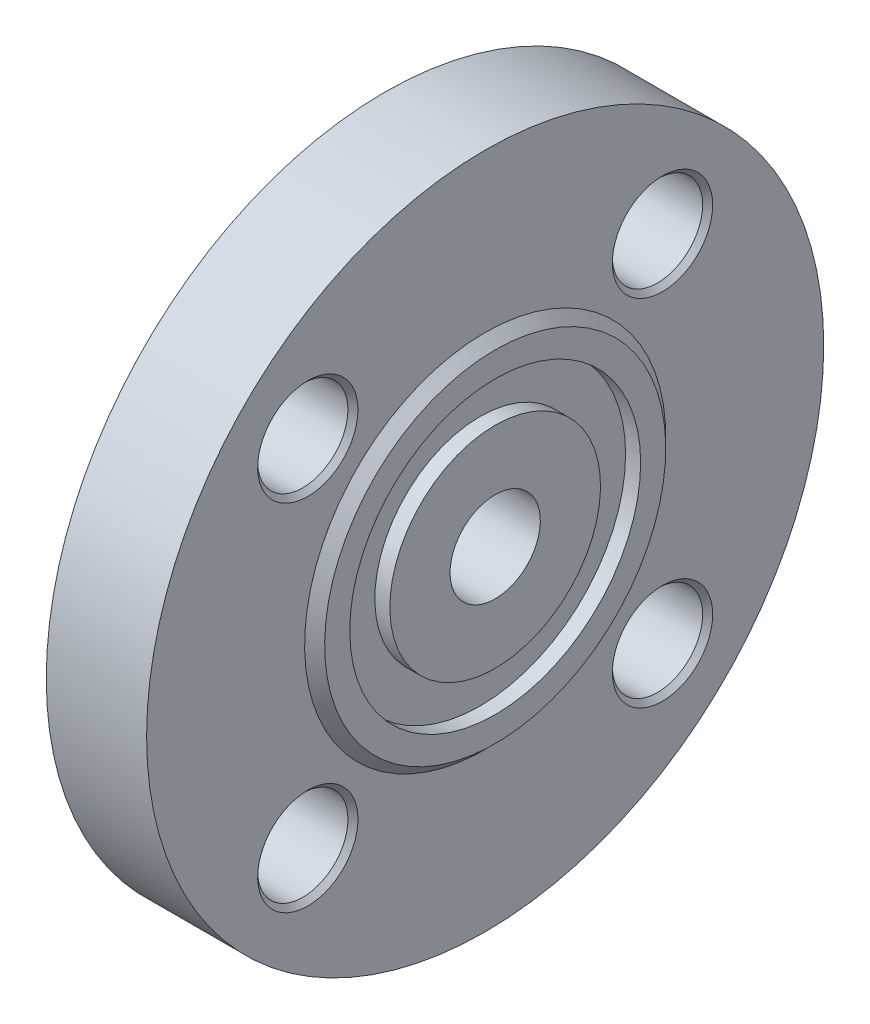
SolidWorks part; units mm, degrees
material "Легированная сталь"
ref_plane "Спереди" through (0, 0, 0) normal (0, 0, 1) x (1, 0, 0)
ref_plane "Сверху" through (0, 0, 0) normal (0, 1, 0) x (1, 0, 0)
ref_plane "Справа" through (0, 0, 0) normal (1, 0, 0) x (0, 0, -1)
sketch "Эскиз1" plane through (0, 0, 0) normal (0, 0, 1) x (1, 0, 0)
  line L0 (0, 0) -> (-82.1524, 0) construction
  line L1 (0, 9) -> (-59.5, 9)
  line L2 (-59.5, 9) -> (-59.5, 11)
  line L3 (-59.5, 11) -> (-50.5, 11)
  line L4 (-50.5, 11) -> (-47.0968, 15.8602)
  line L5 (-47.0968, 15.8602) -> (-25.127, 24.7366)
  line L6 (-22, 29.3725) -> (-22, 67.5)
  line L7 (-22, 67.5) -> (-2, 67.5)
  line L8 (-2, 67.5) -> (-2, 36)
  line L9 (0, 34) -> (-2, 36)
  line L10 (0, 34) -> (0, 29)
  line L11 (-50.5, 11) -> (-50.5, 14.9645) construction
  line L12 (0, 29) -> (-3, 29)
  line L13 (-3, 29) -> (-3, 21)
  line L14 (-3, 21) -> (0, 21)
  line L15 (0, 21) -> (0, 9)
  arc A0 (-25.127, 24.7366) -> (-22, 29.3725) centre (-27, 29.3725) ccw
  point P20 (-22, 26)
  dimension "D16" = 5
  dimension "D1" = 135
  dimension "D2" = 68
  dimension "D3" = 22
  dimension "D4" = 2
  dimension "D5" = 18
  dimension "D6" = 22
  dimension "D7" = 45
  dimension "D8" = 35
  dimension "D9" = 22
  dimension "D10" = 52
  dimension "D11" = 9
  dimension "D12" = 28.5
  dimension "D13" = 42
  dimension "D14" = 58
  dimension "D15" = 3
revolve "Повернуть1" add sketch "Эскиз1" angle 360 about L0
sketch "Эскиз2" plane through (0, 0, 0) normal (0, 0, 1) x (1, 0, 0)
  line L0 (-47.0968, 15.8602) -> (-50.5, 11) construction
  line L1 (-47.0968, 15.8602) -> (-50.5, 11)
  line L2 (-50.5, 11) -> (-50.5, 16)
  line L3 (-50.5, 16) -> (-47.7228, 16)
  line L4 (-45.8497, 16.3641) -> (-47.0968, 15.8602)
  line L5 (-25.127, 24.7366) -> (-47.0968, 15.8602) construction
  line L6 (0, 0) -> (-69.3557, 0) construction
  arc A0 (-47.7228, 16) -> (-45.8497, 16.3641) centre (-47.7228, 21) ccw
  dimension "D2" = 5
  dimension "D1" = 32
revolve "Повернуть2" add sketch "Эскиз2" angle 360 about L6
sketch "Эскиз3" plane through (-2, 0, 0) normal (1, 0, 0) x (0, 0, -1)
  line L0 (35.3553, 35.3553) -> (0, 0) construction
  line L1 (0, 0) -> (0, 50) construction
  circle A0 centre (0, 0) radius 50 construction
  circle A1 centre (35.3553, 35.3553) radius 9
  dimension "D1" = 100
  dimension "D2" = 18
  dimension "D3" = 45
extrude "Вырез-Вытянуть1" cut sketch "Эскиз3" against normal through all
chamfer "Фаска1" distance 1 angle 45 2 edges at (-2, 44.3553, -35.3553) (-22, 26.3553, -35.3553)
pattern_circular "Круговой массив1" count 4 over 360 about axis through (0, 0, 0) along (1, 0, 0) of "Вырез-Вытянуть1", "Фаска1"
